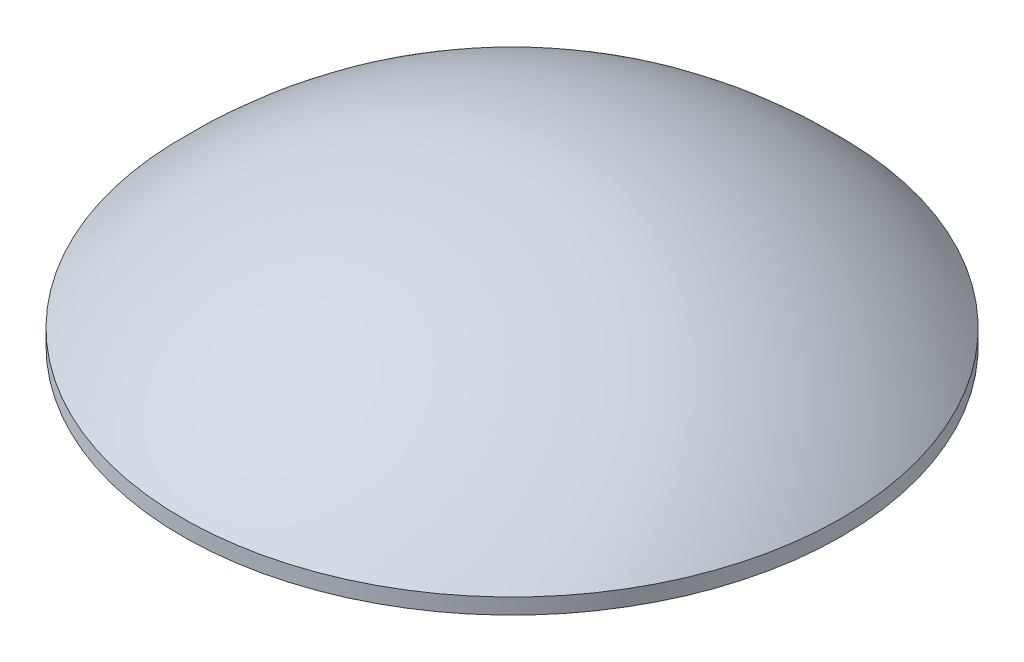
SolidWorks part; units mm, degrees
material "Стекло"
ref_plane "Спереди" through (0, 0, 0) normal (0, 0, 1) x (1, 0, 0)
ref_plane "Сверху" through (0, 0, 0) normal (0, 1, 0) x (1, 0, 0)
ref_plane "Справа" through (0, 0, 0) normal (1, 0, 0) x (0, 0, -1)
sketch "Эскиз1" plane through (0, 0, 0) normal (0, 0, 1) x (1, 0, 0)
  line L0 (0, 0) -> (31.5, 0)
  line L1 (0, 0) -> (0, 15)
  line L2 (31.5, 0) -> (31.5, 1.5)
  circle A2 centre (0, -28.5) radius 43.5
  dimension "D1" = 15
  dimension "D2" = 31.5
  dimension "D3" = 1.5
revolve "Повернуть1" add sketch "Эскиз1" angle 360 about L1
